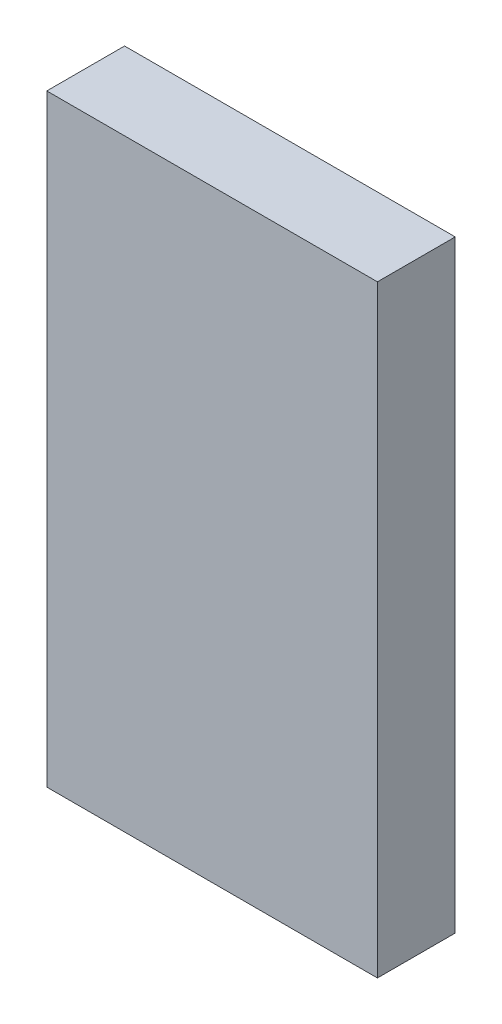
SolidWorks part; units mm, degrees
ref_plane "Front Plane" through (0, 0, 0) normal (0, 0, 1) x (1, 0, 0)
ref_plane "Top Plane" through (0, 0, 0) normal (0, 1, 0) x (1, 0, 0)
ref_plane "Right Plane" through (0, 0, 0) normal (1, 0, 0) x (0, 0, -1)
sketch "Sketch1" plane through (0, 0, 0) normal (0, 1, 0) x (1, 0, 0)
  line L1 (0, 0) -> (17, 0)
  line L2 (0, 0) -> (0, 4)
  line L3 (0, 4) -> (17, 4)
  line L4 (17, 0) -> (17, 4)
  dimension "D1" = 17
  dimension "D2" = 4
extrude "Boss-Extrude1" add sketch "Sketch1" along normal blind 31
